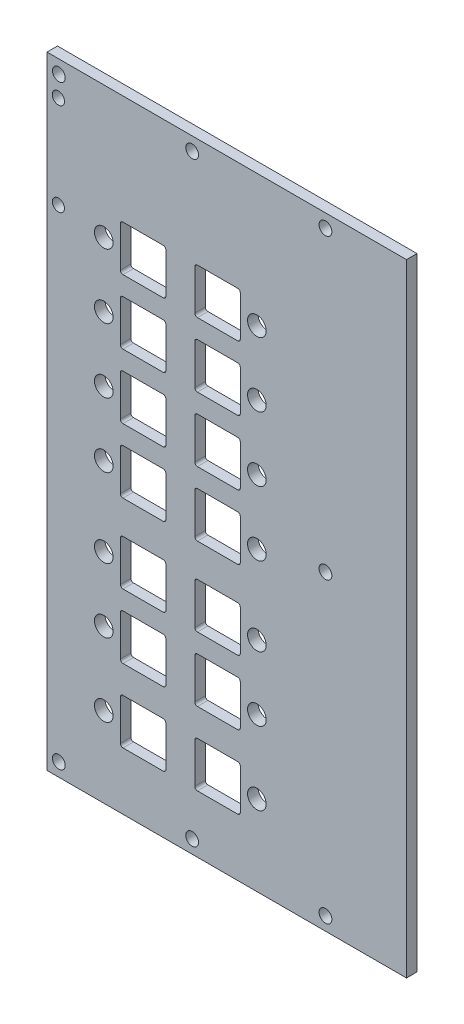
SolidWorks part; units mm, degrees
ref_plane "Front Plane" through (0, 0, 0) normal (0, 0, 1) x (1, 0, 0)
ref_plane "Top Plane" through (0, 0, 0) normal (0, 1, 0) x (1, 0, 0)
ref_plane "Right Plane" through (0, 0, 0) normal (1, 0, 0) x (0, 0, -1)
sketch "Sketch1" plane through (0, 0, 0) normal (0, 0, 1) x (1, 0, 0)
  line L1 (-40.3142, 37.1388) -> (62.4288, 37.1388)
  line L2 (-40.3142, 37.1388) -> (-40.3142, -140.6612)
  line L3 (-40.3142, -140.6612) -> (62.4288, -140.6612)
  line L4 (62.4288, 37.1388) -> (62.4288, -140.6612)
  dimension "D1" = 102.743
  dimension "D2" = 177.8
extrude "Boss-Extrude1" add sketch "Sketch1" along normal blind 3
sketch "Sketch2" plane through (0, 0, 0) normal (0, 0, -1) x (-1, 0, 0)
  line L0 (40.3142, -140.6612) -> (-62.4288, -140.6612) construction
  line L3 (-62.4288, -140.6612) -> (-62.4288, 37.1388) construction
  point P0 (-8.4206, -7.0853)
  point P2 (-14.9206, -0.5853)
  point P6 (-62.4288, -51.7612)
  line B0 (-14.1706, 5.9147) -> (-2.6706, 5.9147)
  line B1 (-14.9206, 5.1647) -> (-14.9206, -6.3353)
  line B2 (-14.1706, -7.0853) -> (-2.6706, -7.0853)
  line B3 (-1.9206, 5.1647) -> (-1.9206, -6.3353)
  arc B4 (-2.6706, 5.9147) -> (-1.9206, 5.1647) centre (-2.6706, 5.1647) cw
  arc B5 (-14.1706, 5.9147) -> (-14.9206, 5.1647) centre (-14.1706, 5.1647) ccw
  arc B6 (-2.6706, -7.0853) -> (-1.9206, -6.3353) centre (-2.6706, -6.3353) ccw
  arc B7 (-14.9206, -6.3353) -> (-14.1706, -7.0853) centre (-14.1706, -6.3353) ccw
  dimension "D1" = 54.0082
  dimension "D2" = 140.0759
sketch_block_instance "caphole-1"
sketch_block "caphole" parameters "D1"=0.75, "D2"=0.75, "D3"=13
extrude "Cut-Extrude1" cut sketch "Sketch2" against normal blind 5.08
pattern_linear "LPattern1" count 2 spacing 21.27 along (-1, 0, 0) count 4 spacing 18.4375 along (0, -1, 0) of "Cut-Extrude1"
sketch "Sketch4" plane through (0, 0, 0) normal (0, 0, -1) x (-1, 0, 0)
  line L0 (-14.9206, 5.1647) -> (-14.9206, -6.3353) construction
  circle A0 centre (-19.6603, -0.5853) radius 2.667
  point P2 (-14.9206, -0.5853)
  dimension "D1" = 5.334
  dimension "D2" = 0
  dimension "D3" = 4.7396
extrude "Cut-Extrude3" cut sketch "Sketch4" against normal blind 5.08
pattern_linear "LPattern3" count 4 spacing 18.4375 along (0, -1, 0) count 2 spacing 43.749 along (-1, 0, 0) of "Cut-Extrude3"
sketch "Sketch5" plane through (0, 0, 0) normal (0, 0, -1) x (-1, 0, 0)
  line L0 (-14.9206, -50.1478) -> (-14.9206, -61.6478) construction
  line L2 (40.3142, -140.6612) -> (-62.4288, -140.6612) construction
  point P2 (-14.9206, -78.388)
  line B0 (-14.1706, -71.888) -> (-2.6706, -71.888)
  line B1 (-14.9206, -72.638) -> (-14.9206, -84.138)
  line B2 (-14.1706, -84.888) -> (-2.6706, -84.888)
  line B3 (-1.9206, -72.638) -> (-1.9206, -84.138)
  arc B4 (-2.6706, -71.888) -> (-1.9206, -72.638) centre (-2.6706, -72.638) cw
  arc B5 (-14.1706, -71.888) -> (-14.9206, -72.638) centre (-14.1706, -72.638) ccw
  arc B6 (-2.6706, -84.888) -> (-1.9206, -84.138) centre (-2.6706, -84.138) ccw
  arc B7 (-14.9206, -84.138) -> (-14.1706, -84.888) centre (-14.1706, -84.138) ccw
  dimension "D1" = 0
  dimension "D2" = 62.2732
sketch_block_instance "caphole-5"
extrude "Cut-Extrude4" cut sketch "Sketch5" against normal blind 5.08
pattern_linear "LPattern5" count 2 spacing 21.27 along (-1, 0, 0) count 2 spacing 18.4375 along (0, -1, 0) of "Cut-Extrude4"
sketch "Sketch6" plane through (0, 0, 0) normal (0, 0, -1) x (-1, 0, 0)
  line L0 (-14.9206, -84.138) -> (-14.9206, -72.638) construction
  circle A0 centre (-19.6603, -78.388) radius 2.667
  point P2 (-14.9206, -78.388)
  dimension "D1" = 5.334
  dimension "D2" = 4.7396
  dimension "D3" = 0
extrude "Cut-Extrude5" cut sketch "Sketch6" against normal blind 5.08
pattern_linear "LPattern6" count 2 spacing 18.4375 along (0, -1, 0) count 2 spacing 43.749 along (-1, 0, 0) of "Cut-Extrude5"
sketch "Sketch7" plane through (0, 0, 0) normal (0, 0, -1) x (-1, 0, 0)
  line L0 (40.3142, -140.6612) -> (-62.4288, -140.6612) construction
  line L2 (40.3142, 37.1388) -> (40.3142, -140.6612) construction
  circle A0 centre (36.936, -136.8512) radius 1.8288
  dimension "D1" = 3.6576
  dimension "D2" = 3.81
  dimension "D3" = 3.3782
extrude "Cut-Extrude6" cut sketch "Sketch7" against normal blind 5.08
pattern_linear "LPattern7" count 3 spacing 85.09 along (0, 1, 0) count 3 spacing 38.1 along (1, 0, 0) skipping (1, 0), (1, 1) of "Cut-Extrude6"
pattern_linear "LPattern8" count 2 spacing 39.335 along (0, -1, 0) count 2 spacing 21.27 along (-1, 0, 0) skipping (0, 1) of "Cut-Extrude4"
pattern_linear "LPattern9" count 2 spacing 39.335 along (0, -1, 0) count 2 spacing 43.749 along (-1, 0, 0) skipping (0, 1) of "Cut-Extrude5"
sketch "Sketch8" plane through (0, 0, 3) normal (0, 0, 1) x (1, 0, 0)
  circle A0 centre (-37.0615, 0.9171) radius 1.7323
  circle A1 centre (-37.0557, 27.4004) radius 1.75
extrude "Cut-Extrude7" cut sketch "Sketch8" against normal blind 10
